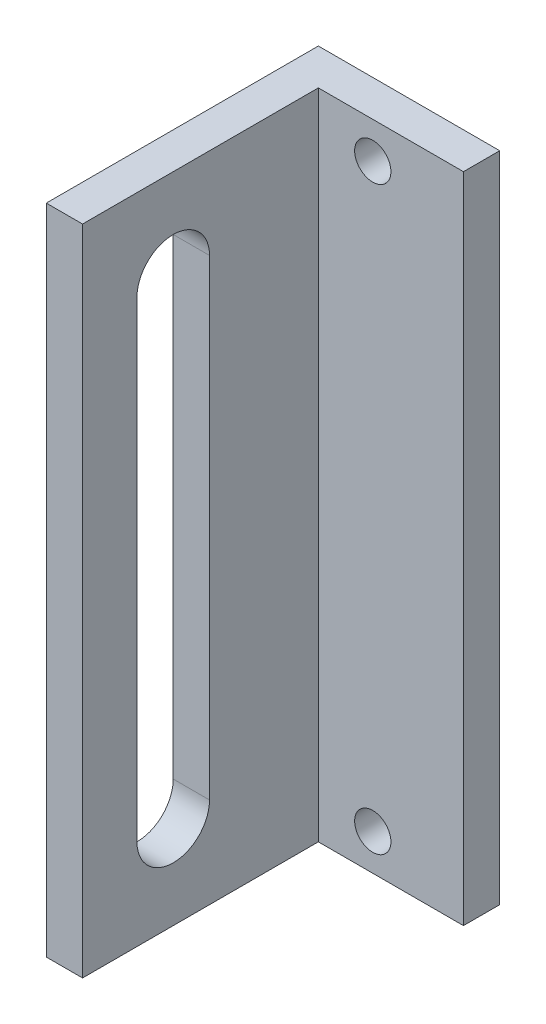
SolidWorks part; units mm, degrees
ref_plane "Front Plane" through (0, 0, 0) normal (0, 0, 1) x (1, 0, 0)
ref_plane "Top Plane" through (0, 0, 0) normal (0, 1, 0) x (1, 0, 0)
ref_plane "Right Plane" through (0, 0, 0) normal (1, 0, 0) x (0, 0, -1)
sketch "Sketch2" plane through (0, 0, 0) normal (0, 0, 1) x (1, 0, 0)
  line L1 (-5, 18) -> (5, 18)
  line L2 (-5, 18) -> (-5, -18)
  line L3 (-5, -18) -> (5, -18)
  line L4 (5, 18) -> (5, -18)
  line L5 (-5, 18) -> (5, -18) construction
  line L6 (-5, -18) -> (5, 18) construction
  point P0 (0, 0)
  dimension "D1" = 10
  dimension "D2" = 36
extrude "Boss-Extrude1" add sketch "Sketch2" along normal blind 2
sketch "Sketch3" plane through (0, 0, 2) normal (0, 0, 1) x (1, 0, 0)
  line L0 (5, 18) -> (-5, 18) construction
  line L1 (-5, 18) -> (-5, -18) construction
  circle A0 centre (0, 16) radius 1
  circle A1 centre (0, -16) radius 1
  dimension "D1" = 2
  dimension "D2" = 2
  dimension "D4" = 2
  dimension "D5" = 5
  dimension "D3" = 32
extrude "Cut-Extrude1" cut sketch "Sketch3" against normal blind 2
sketch "Sketch4" plane through (0, 0, 2) normal (0, 0, 1) x (1, 0, 0)
  line L0 (-5, -18) -> (5, -18) construction
  line L1 (-5, 18) -> (-3, 18)
  line L2 (-5, 18) -> (-5, -18)
  line L3 (-5, -18) -> (-3, -18)
  line L4 (-3, 18) -> (-3, -18)
  dimension "D1" = 2
extrude "Boss-Extrude2" add sketch "Sketch4" along normal blind 13
sketch "Sketch5" plane through (-3, 0, 0) normal (1, 0, 0) x (0, 0, -1)
  line L0 (-10, 13) -> (-10, -13) construction
  line L1 (-8, 13) -> (-8, -13)
  line L2 (-12, 13) -> (-12, -13)
  line L3 (-15, 18) -> (-2, 18) construction
  line L4 (-15, -18) -> (-2, -18) construction
  line L5 (-15, -18) -> (-15, 18) construction
  arc A0 (-8, 13) -> (-12, 13) centre (-10, 13) ccw
  arc A1 (-12, -13) -> (-8, -13) centre (-10, -13) ccw
  point P2 (-10, 0)
  dimension "D1" = 2
  dimension "D3" = 5
  dimension "D2" = 5
  dimension "D4" = 5
extrude "Cut-Extrude2" cut sketch "Sketch5" against normal blind 10
